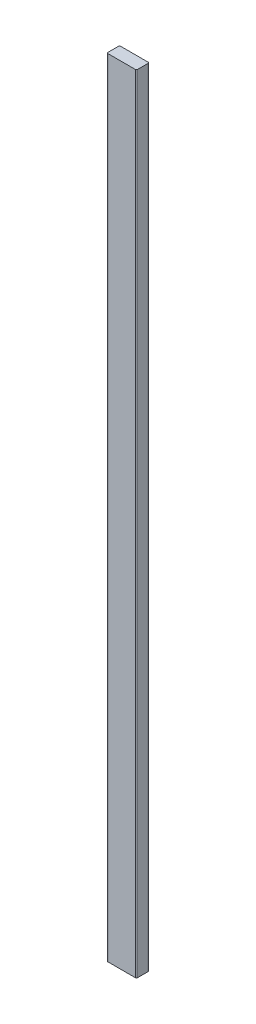
SolidWorks part; units mm, degrees
ref_plane "Front" through (0, 0, 0) normal (0, 0, 1) x (1, 0, 0)
ref_plane "Top" through (0, 0, 0) normal (0, 1, 0) x (1, 0, 0)
ref_plane "Right" through (0, 0, 0) normal (1, 0, 0) x (0, 0, -1)
sketch "Sketch1" plane through (0, 0, 0) normal (0, 1, 0) x (1, 0, 0)
  line L1 (44.45, 19.05) -> (-44.45, 19.05)
  line L2 (44.45, 19.05) -> (44.45, -19.05)
  line L3 (44.45, -19.05) -> (-44.45, -19.05)
  line L4 (-44.45, 19.05) -> (-44.45, -19.05)
  line L5 (44.45, 19.05) -> (-44.45, -19.05) construction
  line L6 (44.45, -19.05) -> (-44.45, 19.05) construction
  point P0 (0, 0)
  dimension "D1" = 38.1
  dimension "D2" = 88.9
extrude "Boss-Extrude1" add sketch "Sketch1" along normal blind 2362.2
hole_wizard "1/4 (0.25) Diameter Hole1" positions "Sketch3" profile "Sketch4" hole size "1/4" standard "ANSI Inch"
sketch "Sketch3" plane through (0, 0, -19.05) normal (0, 0, -1) x (-1, 0, 0)
  line L0 (-44.45, 0) -> (44.45, 0) construction
  point P0 (0, 52.3875)
  point P12 (0, 0)
  point P30 (0, 398.4625)
  point P31 (0, 744.5375)
  point P32 (0, 1090.6125)
  dimension "D1" = 52.3875
  dimension "D2" = 4
sketch "Sketch4" plane through (0, 52.3875, -19.05) normal (1, 0, 0) x (0, 1, 0)
  line L0 (0, 0) -> (0, 38.1)
  line L1 (0, 38.1) -> (3.175, 38.1)
  line L2 (3.175, 38.1) -> (3.175, 0)
  line L5 (3.175, 0) -> (0, 0)
  line L11 (0, -6.35) -> (0, 107.95) construction
  dimension "Thru Hole Dia." = 6.35
  dimension "Thru Hole Depth" = 38.1
fillet "Fillet1" radius 3.175 4 edges at (-44.45, 1181.1, 19.05) (-44.45, 1181.1, -19.05) (44.45, 1181.1, 19.05) (44.45, 1181.1, -19.05)
